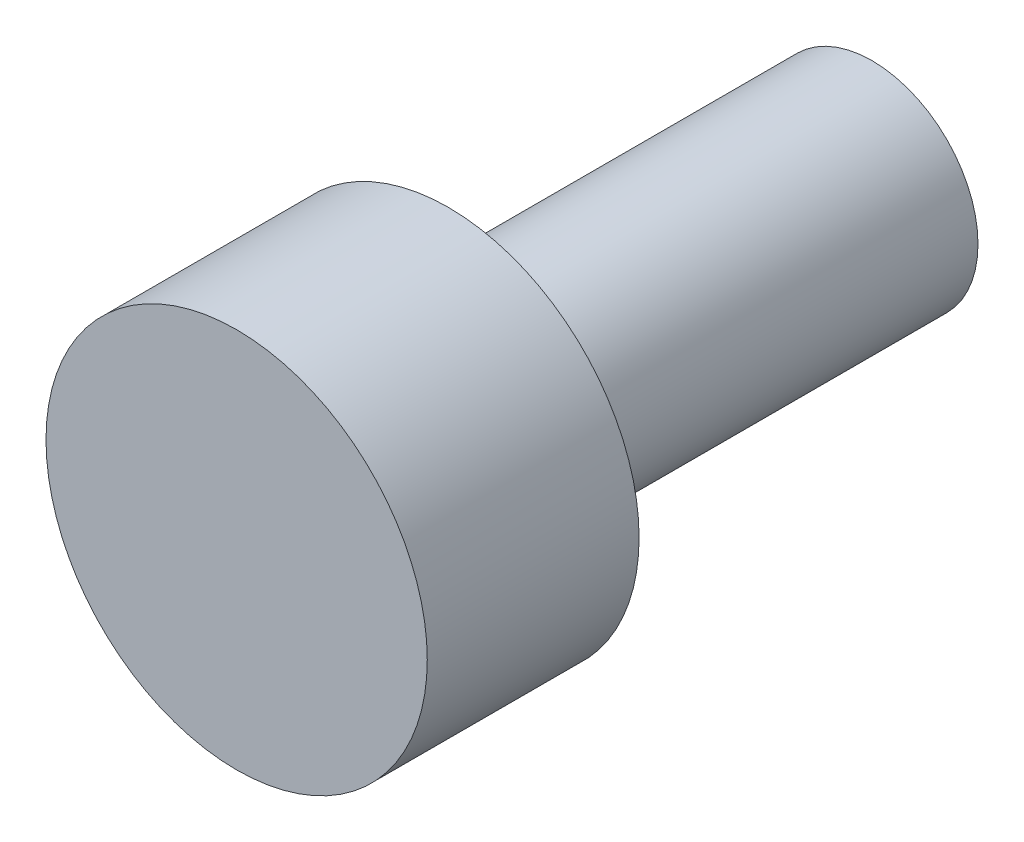
SolidWorks part; units mm, degrees
ref_plane "前视基准面" through (0, 0, 0) normal (0, 0, 1) x (1, 0, 0)
ref_plane "上视基准面" through (0, 0, 0) normal (0, 1, 0) x (1, 0, 0)
ref_plane "右视基准面" through (0, 0, 0) normal (1, 0, 0) x (0, 0, -1)
sketch "草图1" plane through (0, 0, 0) normal (0, 0, 1) x (1, 0, 0)
  circle A0 centre (0, 0) radius 1.8
extrude "凸台-拉伸1" add sketch "草图1" along normal blind 2
sketch "草图2" plane through (0, 0, 0) normal (0, 0, -1) x (-1, 0, 0)
  circle A0 centre (0, 0) radius 1
extrude "凸台-拉伸3" add sketch "草图2" along normal blind 4
